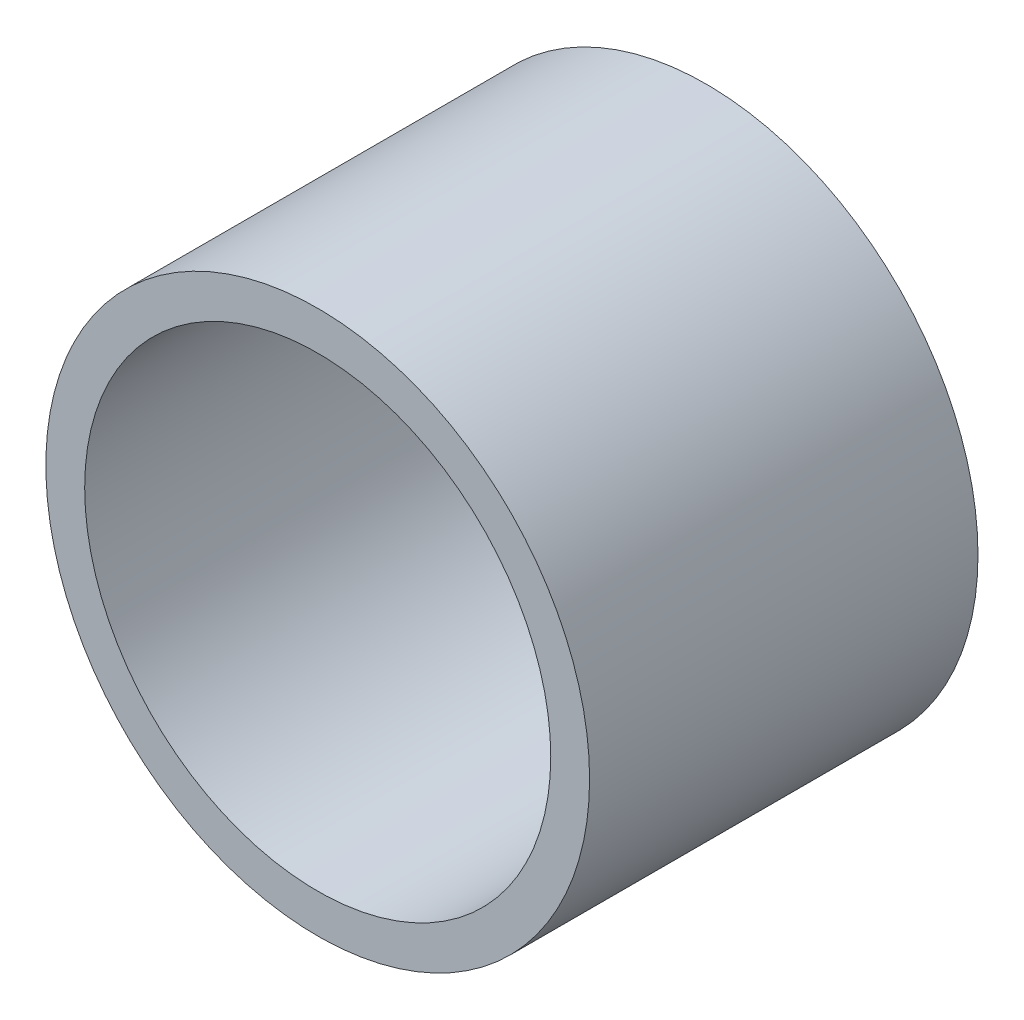
SolidWorks part; units mm, degrees
ref_plane "Спереди" through (0, 0, 0) normal (0, 0, 1) x (1, 0, 0)
ref_plane "Сверху" through (0, 0, 0) normal (0, 1, 0) x (1, 0, 0)
ref_plane "Справа" through (0, 0, 0) normal (1, 0, 0) x (0, 0, -1)
sketch "Эскиз1" plane through (0, 0, 0) normal (0, 0, 1) x (1, 0, 0)
  circle A0 centre (0, 0) radius 3.5
  circle A1 centre (0, 0) radius 3
extrude "Бобышка-Вытянуть1" add sketch "Эскиз1" along normal blind 5
